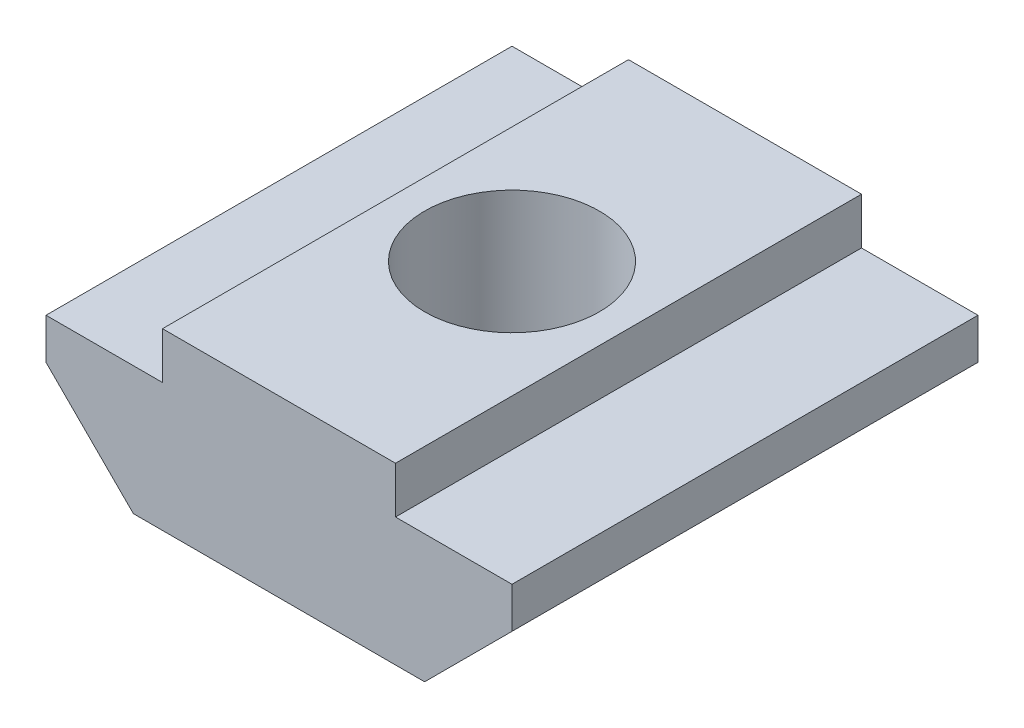
SolidWorks part; units mm, degrees
ref_plane "前视基准面" through (0, 0, 0) normal (0, 0, 1) x (1, 0, 0)
ref_plane "上视基准面" through (0, 0, 0) normal (0, 1, 0) x (1, 0, 0)
ref_plane "右视基准面" through (0, 0, 0) normal (1, 0, 0) x (0, 0, -1)
other "Configuration Table"
sketch "草图1" plane through (0, 0, 0) normal (0, 0, 1) x (1, 0, 0)
  line L0 (0, 14.5556) -> (0, -15) construction
  line L1 (5, -4.4) -> (-5, -4.4)
  line L2 (-5, -4.4) -> (-8, -1.4)
  line L3 (-8, -1.4) -> (-8, 0)
  line L4 (-8, 0) -> (-4, 0)
  line L5 (-4, 0) -> (-4, 1.6)
  line L7 (4, 0) -> (4, 1.6)
  line L8 (8, 0) -> (4, 0)
  line L9 (8, -1.4) -> (8, 0)
  line L10 (5, -4.4) -> (8, -1.4)
  line L11 (-4, 1.6) -> (4, 1.6)
  point P3 (-4.4077, -4.4)
  point P11 (-4.7962, -4.4)
  dimension "D1" = 1.6
  dimension "D2" = 6
  dimension "D3" = 16
  dimension "D4" = 8
  dimension "D5" = 135
  dimension "D6" = 1.4
extrude "凸台-拉伸1" add sketch "草图1" along normal blind 16
sketch "草图2" plane through (0, 0, 0) normal (0, 1, 0) x (1, 0, 0)
  circle A0 centre (0, -8) radius 3
  dimension "D2" = 6
  dimension "D1" = 8
extrude "切除-拉伸1" cut sketch "草图2" against normal through all both and the other way through all
